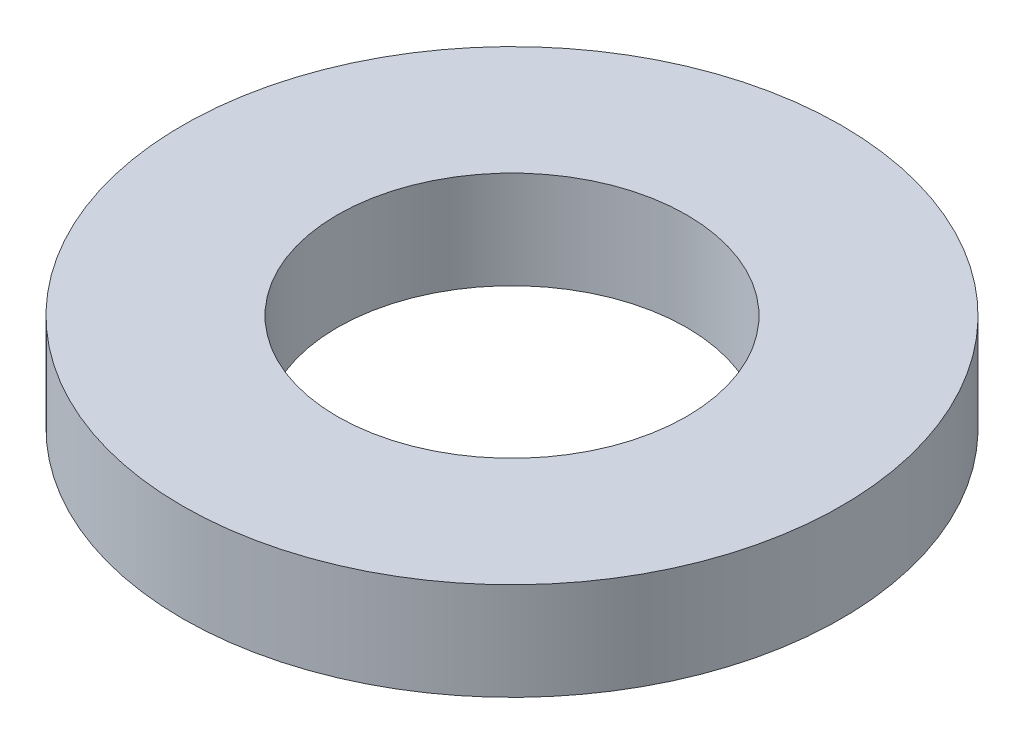
SolidWorks part; units mm, degrees
ref_plane "Front Plane" through (0, 0, 0) normal (0, 0, 1) x (1, 0, 0)
ref_plane "Top Plane" through (0, 0, 0) normal (0, 1, 0) x (1, 0, 0)
ref_plane "Right Plane" through (0, 0, 0) normal (1, 0, 0) x (0, 0, -1)
sketch "Sketch1" plane through (0, 0, 0) normal (0, 1, 0) x (1, 0, 0)
  circle A0 centre (0, 0) radius 6.35
  dimension "OD" = 12.7
extrude "Boss-Extrude1" add sketch "Sketch1" along normal blind 1.8796
sketch "Sketch5" plane through (0, 1.8796, 0) normal (0, 1, 0) x (-1, 0, 0)
  circle A0 centre (0, 0) radius 3.3655
  dimension "ID" = 6.731
extrude "Cut-Extrude1" cut sketch "Sketch5" against normal through all
